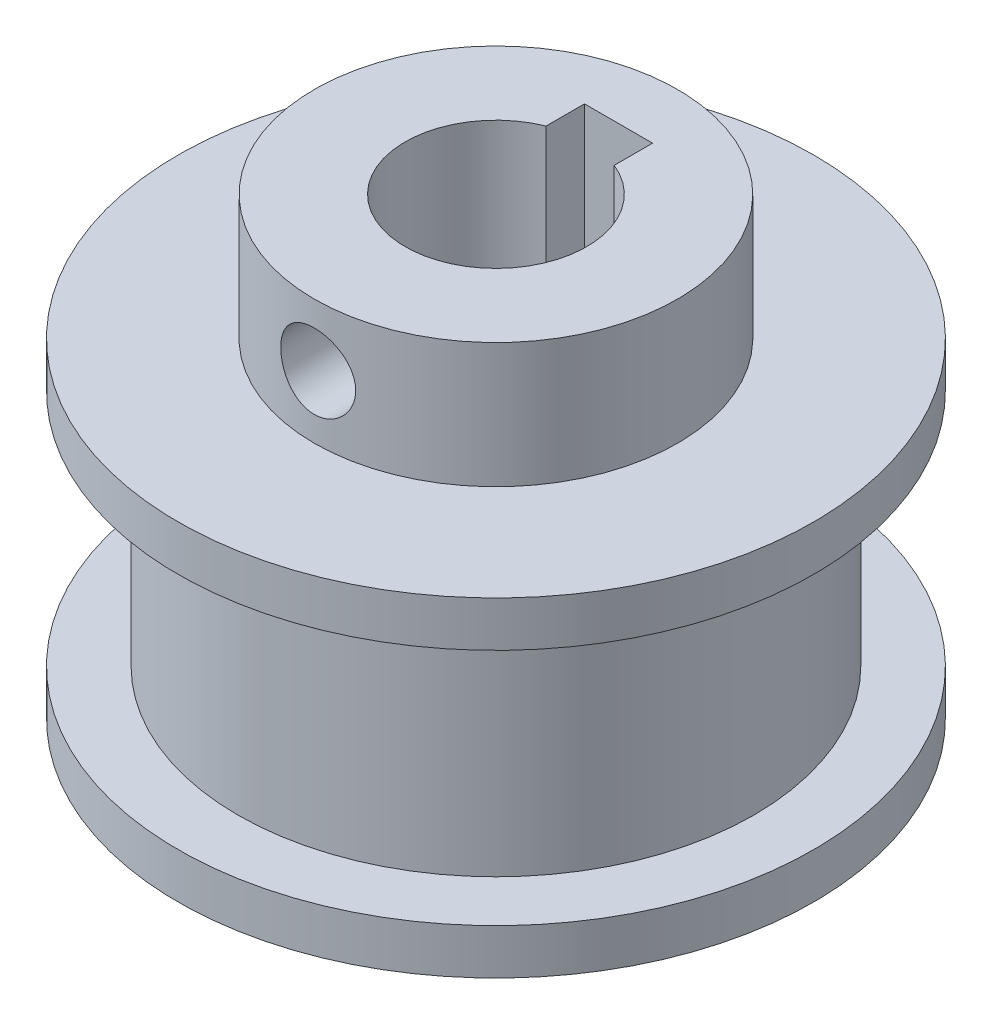
SolidWorks part; units mm, degrees
ref_plane "Front Plane" through (0, 0, 0) normal (0, 0, 1) x (1, 0, 0)
ref_plane "Top Plane" through (0, 0, 0) normal (0, 1, 0) x (1, 0, 0)
ref_plane "Right Plane" through (0, 0, 0) normal (1, 0, 0) x (0, 0, -1)
sketch "Sketch1" plane through (0, 0, 0) normal (0, 1, 0) x (1, 0, 0)
  circle A0 centre (0, 0) radius 14
  dimension "D1" = 28
extrude "Boss-Extrude1" add sketch "Sketch1" along normal blind 14.5
sketch "Sketch2" plane through (0, 14.5, 0) normal (0, 1, 0) x (1, 0, 0)
  circle A0 centre (0, 0) radius 8
  dimension "D1" = 16
extrude "Boss-Extrude2" add sketch "Sketch2" along normal blind 5.5
sketch "Sketch3" plane through (0, 0, 0) normal (1, 0, 0) x (0, 0, -1)
  line L0 (0, 14.5) -> (0, 0) construction
  line L1 (-16.635, 12.5) -> (-11.365, 12.5)
  line L2 (-16.635, 12.5) -> (-16.635, 2)
  line L3 (-16.635, 2) -> (-11.365, 2)
  line L4 (-11.365, 12.5) -> (-11.365, 2)
  line L5 (-16.635, 12.5) -> (-11.365, 2) construction
  line L6 (-16.635, 2) -> (-11.365, 12.5) construction
  line L7 (-14, 14.5) -> (-14, 0) construction
  line L8 (-14, 14.5) -> (-14, 0) construction
  line L10 (14, 14.5) -> (-14, 14.5) construction
  point P0 (-14, 7.25)
  dimension "D1" = 10.5
  dimension "D2" = 5.27
revolve "Cut-Revolve1" cut sketch "Sketch3" angle 360 about L0
sketch "Sketch4" plane through (0, 20, 0) normal (0, 1, 0) x (1, 0, 0)
  circle A0 centre (0, 0) radius 4
  dimension "D1" = 8
extrude "Cut-Extrude1" cut sketch "Sketch4" against normal through all
sketch "Sketch5" plane through (0, 20, 0) normal (0, 1, 0) x (1, 0, 0)
  line L0 (0, 4) -> (0, 0) construction
  line L1 (-1.5, 5.4) -> (1.5, 5.4)
  line L2 (-1.5, 5.4) -> (-1.5, 2.6)
  line L3 (-1.5, 2.6) -> (1.5, 2.6)
  line L4 (1.5, 5.4) -> (1.5, 2.6)
  line L5 (-1.5, 5.4) -> (1.5, 2.6) construction
  line L6 (-1.5, 2.6) -> (1.5, 5.4) construction
  circle A0 centre (0, 0) radius 4 construction
  point P0 (0, 4)
  dimension "D1" = 2.8
  dimension "D2" = 3
extrude "Cut-Extrude2" cut sketch "Sketch5" against normal through all
sketch "Sketch9" plane through (0, 0, 0) normal (0, 0, 1) x (1, 0, 0)
  line L0 (-8, 17.25) -> (8, 17.25) construction
  line L1 (-8, 20) -> (-8, 14.5) construction
  line L2 (8, 14.5) -> (8, 20) construction
  point P6 (0, 17.25)
hole_wizard "M4 Tapped Hole1" positions "3DSketch1" profile "Sketch11" tap size "M4" standard "DIN"
sketch3d "3DSketch1"
  point P4 (0, 17.25, 8)
sketch "Sketch11" plane through (0, 17.25, 8) normal (1, 0, 0) x (0, -1, 0)
  line L0 (0, 0) -> (0, 5.9914)
  line L1 (0, 5.9914) -> (1.65, 5)
  line L2 (1.65, 5) -> (1.65, 0)
  line L5 (1.65, 0) -> (0, 0)
  line L10 (0, 5.9914) -> (-1.65, 5) construction
  line L11 (0, -6.35) -> (0, 107.95) construction
  dimension "Tap Drill Dia." = 3.3
  dimension "Tap Drill Depth" = 5
  dimension "Drill Angle" = 118
